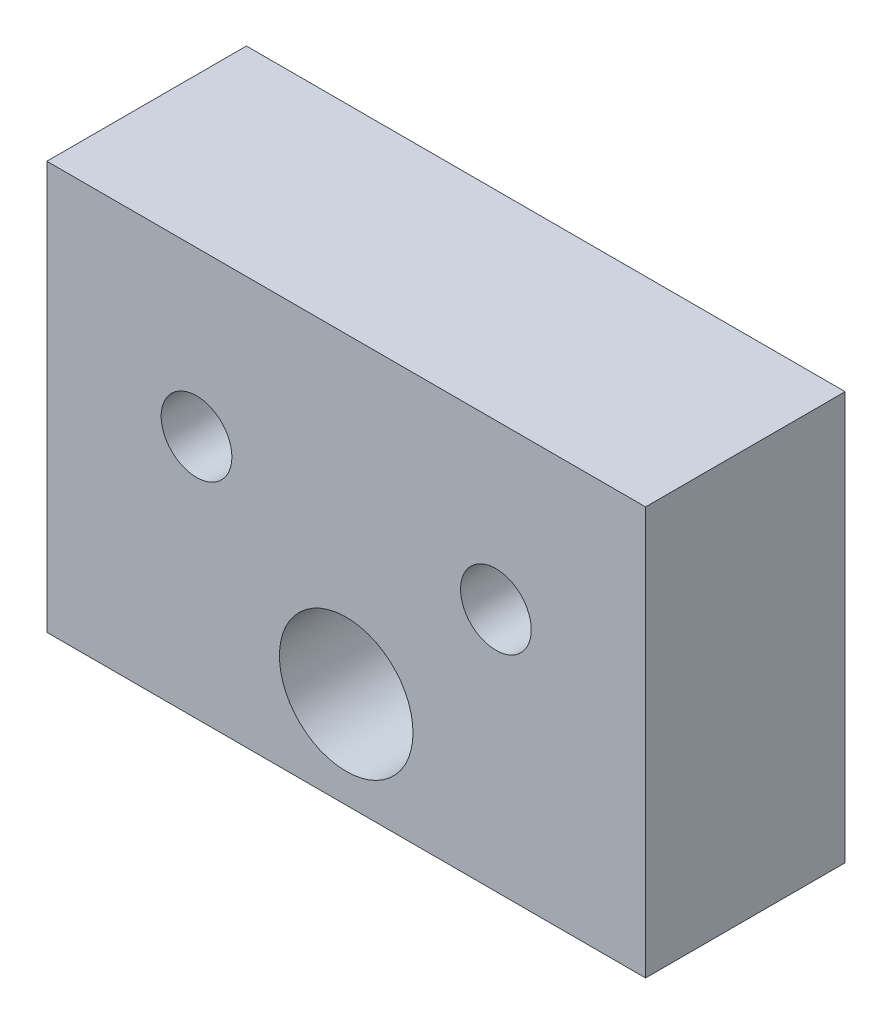
SolidWorks part; units mm, degrees
material "Acrylic (Medium-high impact)"
ref_plane "Front Plane" through (0, 0, 0) normal (0, 0, 1) x (1, 0, 0)
ref_plane "Top Plane" through (0, 0, 0) normal (0, 1, 0) x (1, 0, 0)
ref_plane "Right Plane" through (0, 0, 0) normal (1, 0, 0) x (0, 0, -1)
sketch "Sketch1" plane through (0, 0, 0) normal (0, 0, 1) x (1, 0, 0)
  line L2 (38.1, -12.224) -> (38.1, 12.224)
  line L4 (-38.1, -12.224) -> (-38.1, 12.224)
  line L8 (-38.1, -12.224) -> (38.1, -12.224)
  line L11 (-38.1, 39.7023) -> (-38.1, 12.224)
  line L12 (38.1, 12.224) -> (38.1, 39.7023)
  line L13 (-38.1, 39.7023) -> (-38.1, 49.2259)
  line L14 (-38.1, 39.7023) -> (38.1, 39.7023)
  line L16 (-38.1, 49.2259) -> (38.1, 49.2259)
  line L18 (38.1, 39.7023) -> (38.1, 49.2259)
  circle A0 centre (0, 0) radius 8.5
  circle A1 centre (19.05, 18.8743) radius 4.5
  circle A2 centre (-19.05, 18.8743) radius 4.5
  point P0 (0, 0)
  point P6 (-38.1, 0)
  dimension "D3" = 17
  dimension "D4" = 9
  dimension "D1" = 76.2
  dimension "D2" = 20.828
  dimension "D5" = 19.05
  dimension "D7" = 19.05
extrude "Boss-Extrude1" add sketch "Sketch1" along normal mid plane 25.4 contours L14 L11 L4 L8 L2 L12 A2 A1 A0
